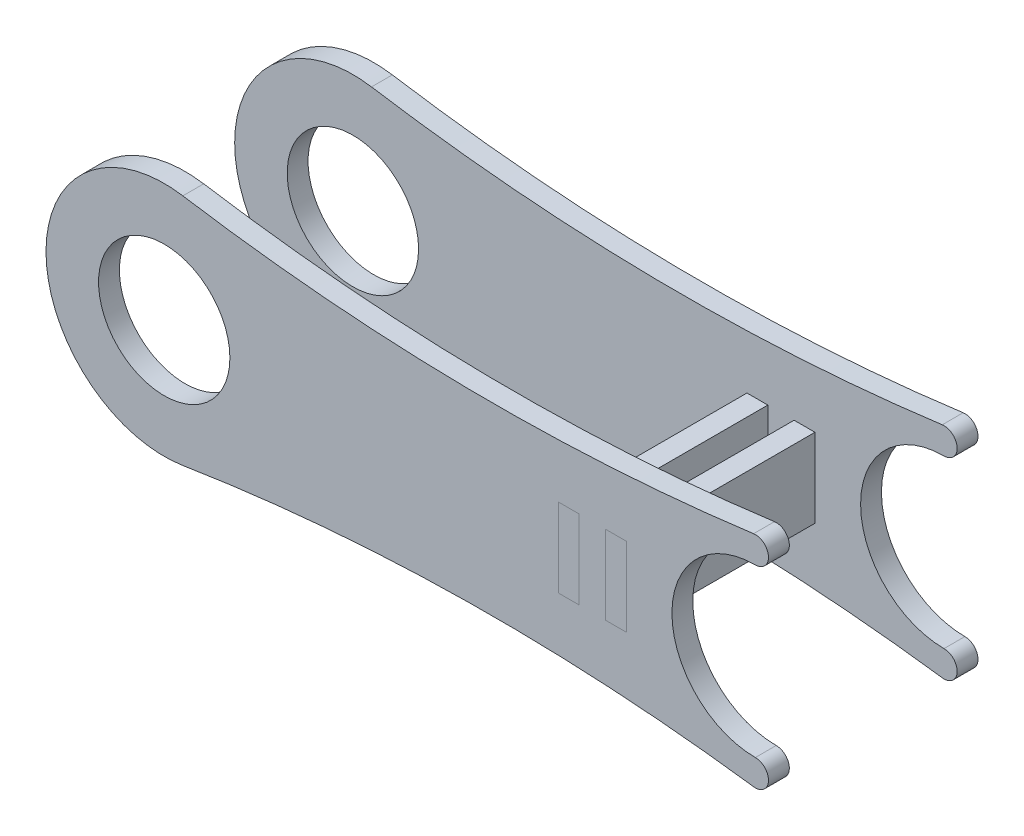
SolidWorks part; units mm, degrees
ref_plane "Front Plane" through (0, 0, 0) normal (0, 0, 1) x (1, 0, 0)
ref_plane "Top Plane" through (0, 0, 0) normal (0, 1, 0) x (1, 0, 0)
ref_plane "Right Plane" through (0, 0, 0) normal (1, 0, 0) x (0, 0, -1)
sketch "Sketch1" plane through (0, 0, 0) normal (0, 0, 1) x (1, 0, 0)
  line L17 (0, 0) -> (90, 0) construction
  line L22 (67.175, 6) -> (67.175, -6)
  line L23 (67.175, 6) -> (70.35, 6)
  line L28 (67.175, -6) -> (70.35, -6)
  line L29 (70.35, 6) -> (70.35, -6)
  line L30 (67.175, 6) -> (70.35, -6) construction
  line L31 (67.175, -6) -> (70.35, 6) construction
  line L32 (60, 6) -> (60, -6)
  line L33 (60, 6) -> (63.175, 6)
  line L34 (60, -6) -> (63.175, -6)
  line L35 (63.175, 6) -> (63.175, -6)
  line L36 (60, 6) -> (63.175, -6) construction
  line L37 (60, -6) -> (63.175, 6) construction
  circle A13 centre (0, 0) radius 10
  arc A14 (2.8312, 17.7759) -> (2.8312, -17.7759) centre (0, 0) ccw
  arc A17 (89.7352, 16.6824) -> (90, 12.7) centre (90, 14.7) cw
  arc A18 (2.8312, 17.7759) -> (89.7352, 16.6824) centre (50.0181, 314.0417) ccw
  arc A19 (90, -12.7) -> (90, 12.7) centre (90, 0) cw
  arc A20 (89.7352, -16.6824) -> (90, -12.7) centre (90, -14.7) ccw
  arc A21 (2.8312, -17.7759) -> (89.7352, -16.6824) centre (50.0181, -314.0417) cw
  point P2 (27.8821, -6.1283)
  point P4 (0, 0)
  point P5 (101.3237, 8.3848)
  point P9 (68.7625, 0)
  point P11 (29.4756, -16.7511)
  point P12 (61.5875, 0)
  point P13 (111.9254, 19.9253)
  point P17 (117.5406, 10.5381)
  point P18 (0, 0)
  point P22 (0, 0)
  point P24 (94.076, -38.8844)
  point P29 (104.9688, 22.4702)
  point P30 (106.1266, 18.1744)
  point P31 (2.1451, -29.9977)
  point P35 (134.2179, -19.6125)
  point P36 (94.6, -10)
  point P37 (103.6727, -23.8831)
  point P38 (116.513, 31.9579)
  point P39 (103.428, -13.8175)
  point P40 (102.56, 18.636)
  point P41 (86.9577, 10)
  point P42 (85.3776, -10)
  point P43 (68.7641, -14.7)
  point P44 (65.5927, 0)
  point P46 (0, 0)
  dimension "D1" = 20
  dimension "D2" = 2
  dimension "D5" = 12.7
  dimension "D7" = 90
  dimension "D9" = 12
  dimension "D11" = 4
  dimension "D3" = 60
  dimension "D4" = 18
  dimension "D6" = 300
  dimension "D8" = 3.175
extrude "Boss-Extrude1" add sketch "Sketch1" along normal blind 3.175
ref_plane "Plane1" through (0, 0, -12.775) normal (0, 0, -1) x (-1, 0, 0)
mirror "Mirror3" about plane through (0, 0, -12.775) normal (0, 0, -1) of bodies 101
sketch "Sketch2" plane through (0, 0, 3.175) normal (0, 0, 1) x (1, 0, 0)
  line L13 (60, 6) -> (60, -6)
  line L14 (60, 6) -> (63.175, 6)
  line L15 (60, -6) -> (63.175, -6)
  line L16 (63.175, 6) -> (63.175, -6)
  line L17 (67.175, -6) -> (67.175, 6)
  line L18 (67.175, -6) -> (70.35, -6)
  line L19 (67.175, 6) -> (70.35, 6)
  line L20 (70.35, -6) -> (70.35, 6)
  line L21 (70.35, -6) -> (70.35, 6) construction
  line L22 (63.175, -6) -> (63.175, 6) construction
ref_plane "Plane2" through (0, 0, -12.775) normal (0, 0, -1) x (-1, 0, 0)
extrude "Boss-Extrude2" add sketch "Sketch2" against normal up to surface (31.9 mm away) separate body contours L16 L15 L13 L14 | L20 L19 L17 L18 up to face at (68.7625, 0, -28.725)
